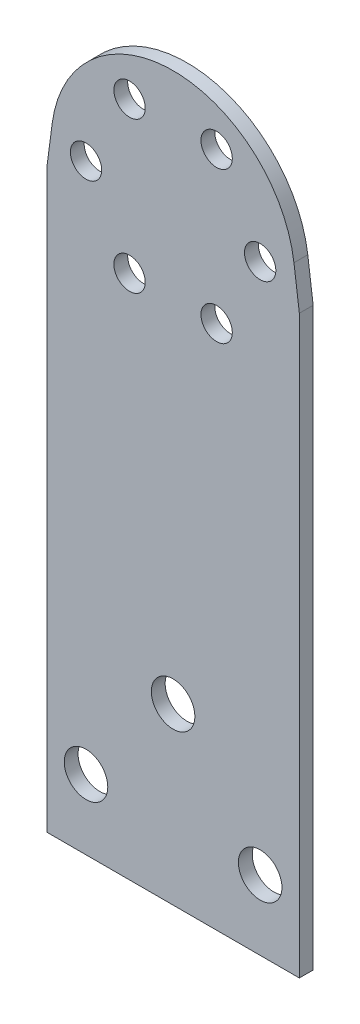
SolidWorks part; units mm, degrees
ref_plane "Front Plane" through (0, 0, 0) normal (0, 0, 1) x (1, 0, 0)
ref_plane "Top Plane" through (0, 0, 0) normal (0, 1, 0) x (1, 0, 0)
ref_plane "Right Plane" through (0, 0, 0) normal (1, 0, 0) x (0, 0, -1)
sketch "Sketch1" plane through (0, 0, 0) normal (0, 0, 1) x (1, 0, 0)
  circle A0 centre (0, 0) radius 14
  dimension "D1" = 28
extrude "Boss-Extrude1" add sketch "Sketch1" along normal mid plane 1.5875
sketch "Sketch2" plane through (0, 0, 0.7937) normal (0, 0, 1) x (1, 0, 0)
  line L0 (-13.8803, 1.8267) -> (-22.4573, -63.3476)
  line L1 (-17.5, -69) -> (17.5, -69)
  line L2 (22.4573, -63.3476) -> (13.8803, 1.8267)
  line L3 (13.8803, 1.8267) -> (-13.8803, 1.8267)
  line L4 (-22.5, -64) -> (22.5, -64) construction
  line L5 (0, -69) -> (0, -49) construction
  line L6 (-10, -61) -> (10, -61) construction
  circle A0 centre (0, 0) radius 14 construction
  arc A1 (-22.4573, -63.3476) -> (-17.5, -69) centre (-17.5, -64) ccw
  arc A2 (17.5, -69) -> (22.4573, -63.3476) centre (17.5, -64) ccw
  circle A4 centre (-10, -61) radius 2.5
  circle A5 centre (10, -61) radius 2.5
  circle A6 centre (0, -49) radius 2.5
  point P17 (0, -61)
  dimension "D4" = 10
  dimension "D2" = 20
  dimension "D3" = 5
  dimension "D6" = 5
  dimension "D7" = 5
  dimension "D1" = 64
  dimension "D5" = 35
  dimension "D8" = 12
  dimension "D9" = 8
extrude "Boss-Extrude2" add sketch "Sketch2" against normal through all
hole_wizard "M3 Clearance Hole1" positions "Sketch3" profile "Sketch4" hole size "M3" standard "ANSI Metric"
sketch "Sketch3" plane through (0, 0, 0.7937) normal (0, 0, 1) x (1, 0, 0)
  line L1 (-5, 8.6603) -> (-10, 0) construction
  line L2 (-10, 0) -> (-5, -8.6603) construction
  line L3 (-5, -8.6603) -> (5, -8.6603) construction
  line L4 (5, -8.6603) -> (10, 0) construction
  line L5 (10, 0) -> (5, 8.6603) construction
  line L6 (5, 8.6603) -> (-5, 8.6603) construction
  circle A0 centre (0, 0) radius 8.6603 construction
  circle A1 centre (0, 0) radius 10
  point P3 (-5, 8.6603)
  point P4 (-10, 0)
  point P5 (-5, -8.6603)
  point P6 (5, -8.6603)
  point P7 (10, 0)
  point P8 (5, 8.6603)
  dimension "D1" = 20
sketch "Sketch4" plane through (5, 8.6603, 0.7937) normal (1, 0, 0) x (0, -1, 0)
  line L0 (0, 0) -> (0, 1.5875)
  line L1 (0, 1.5875) -> (1.8, 1.5875)
  line L2 (1.8, 1.5875) -> (1.8, 0)
  line L5 (1.8, 0) -> (0, 0)
  line L11 (0, -6.35) -> (0, 107.95) construction
  dimension "Thru Hole Dia." = 3.6
  dimension "Thru Hole Depth" = 1.5875
sketch "Sketch5" plane through (0, 0, -0.7937) normal (0, 0, -1) x (-1, 0, 0)
  line L0 (17.5, -69) -> (-17.5, -69) construction
  line L1 (-14.5, -2.8821) -> (14.5, -2.8821)
  line L2 (-14.5, -2.8821) -> (-14.5, -69)
  line L3 (-14.5, -69) -> (14.5, -69)
  line L4 (14.5, -2.8821) -> (14.5, -69)
  line L5 (13.8803, 1.8267) -> (22.4573, -63.3476) construction
  line L9 (-13.8803, 1.8267) -> (-22.4573, -63.3476)
  line L10 (-17.5, -69) -> (17.5, -69)
  line L11 (22.4573, -63.3476) -> (13.8803, 1.8267)
  line L12 (-13.8803, 1.8267) -> (-22.4573, -63.3476)
  line L13 (-17.5, -69) -> (17.5, -69)
  line L14 (22.4573, -63.3476) -> (13.8803, 1.8267)
  arc A3 (13.8803, 1.8267) -> (-13.8803, 1.8267) centre (0, 0) ccw
  arc A4 (-22.4573, -63.3476) -> (-17.5, -69) centre (-17.5, -64) ccw
  arc A5 (17.5, -69) -> (22.4573, -63.3476) centre (17.5, -64) ccw
  arc A6 (13.8803, 1.8267) -> (-13.8803, 1.8267) centre (0, 0) ccw
  arc A7 (-22.4573, -63.3476) -> (-17.5, -69) centre (-17.5, -64) ccw
  arc A8 (17.5, -69) -> (22.4573, -63.3476) centre (17.5, -64) ccw
  point P6 (0, -69)
  line M18 (-13.8803, 1.8267) -> (-22.4573, -63.3476)
  arc M19 (-22.4573, -63.3476) -> (-17.5, -69) centre (-17.5, -64) ccw
  arc M21 (17.5, -69) -> (22.4573, -63.3476) centre (17.5, -64) ccw
  line M22 (22.4573, -63.3476) -> (13.8803, 1.8267)
  dimension "D1" = 29
  dimension "D2" = 0
extrude "Cut-Extrude1" cut sketch "Sketch5" against normal blind 10 contours L2 M18 M19 | L4 M22 M21
